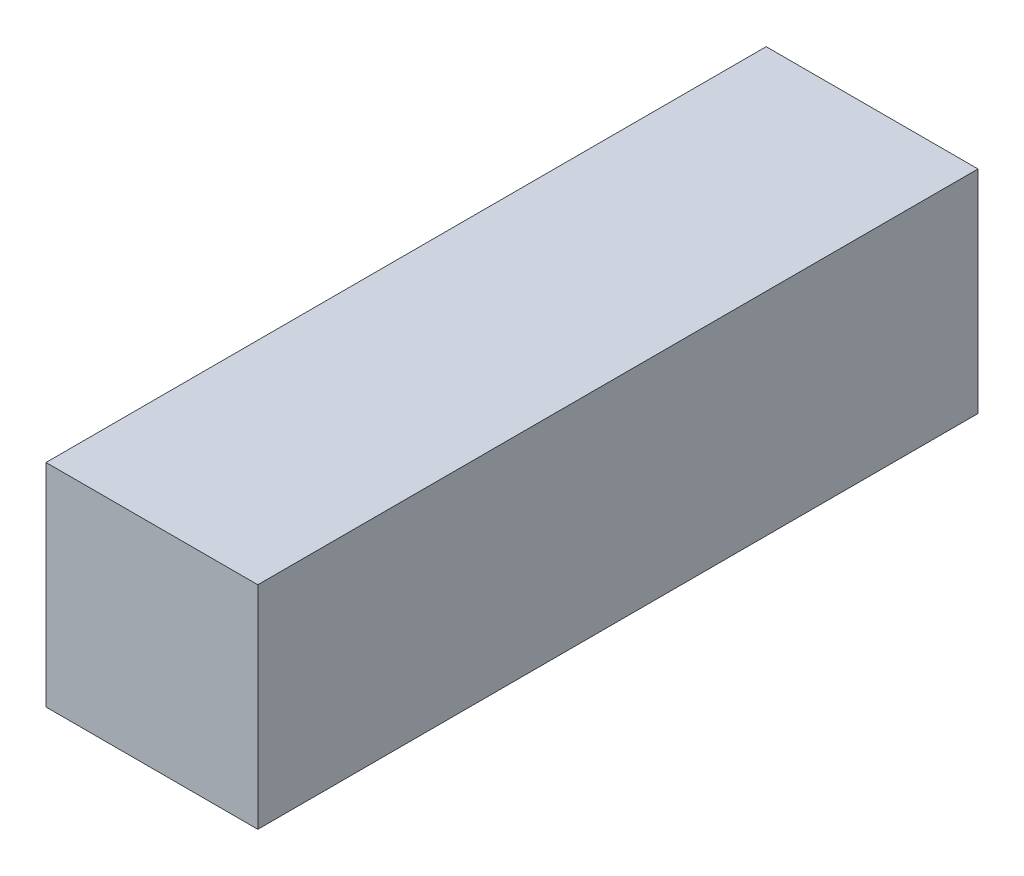
SolidWorks part; units mm, degrees
ref_plane "Front Plane" through (0, 0, 0) normal (0, 0, 1) x (1, 0, 0)
ref_plane "Top Plane" through (0, 0, 0) normal (0, 1, 0) x (1, 0, 0)
ref_plane "Right Plane" through (0, 0, 0) normal (1, 0, 0) x (0, 0, -1)
sketch "Sketch1" plane through (0, 0, 0) normal (0, 0, 1) x (1, 0, 0)
  line L1 (-12, 12) -> (-32, 12)
  line L2 (-12, 12) -> (-12, 32)
  line L3 (-12, 32) -> (-32, 32)
  line L4 (-32, 12) -> (-32, 32)
  dimension "D1" = 20
  dimension "D2" = 20
extrude "Boss-Extrude1" add sketch "Sketch1" along normal up to surface (68 mm away)
